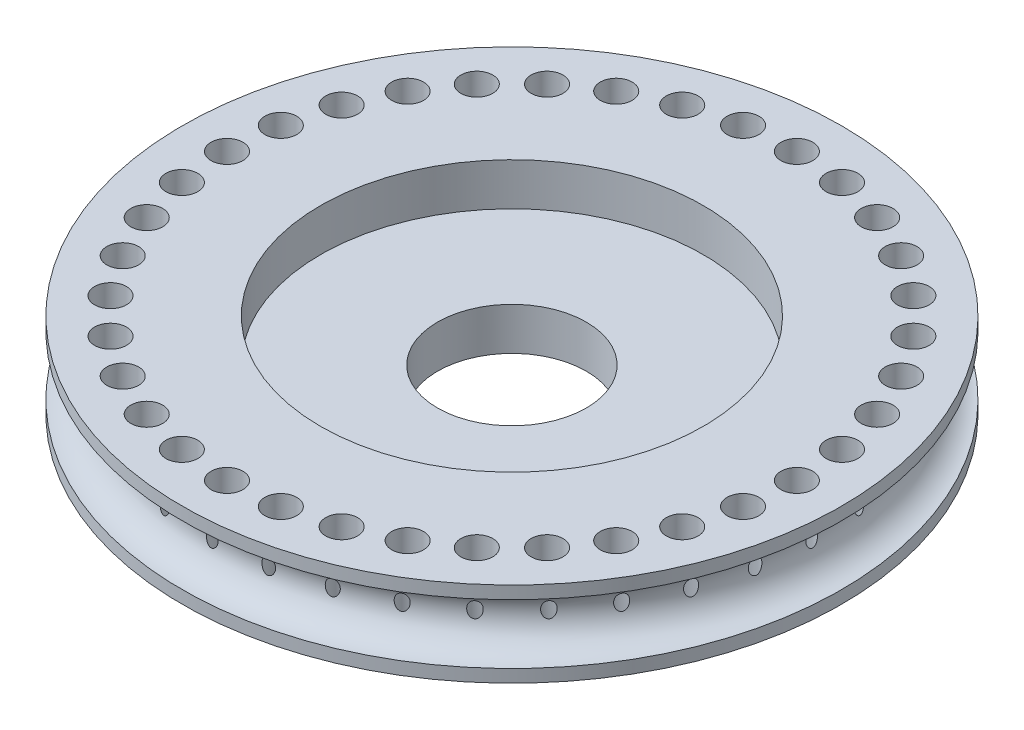
SolidWorks part; units mm, degrees
ref_plane "Front Plane" through (0, 0, 0) normal (0, 0, 1) x (1, 0, 0)
ref_plane "Top Plane" through (0, 0, 0) normal (0, 1, 0) x (1, 0, 0)
ref_plane "Right Plane" through (0, 0, 0) normal (1, 0, 0) x (0, 0, -1)
sketch "Sketch1" plane through (0, 0, 0) normal (0, 0, 1) x (1, 0, 0)
  line L0 (0, 0) -> (0, 11.2256) construction
  line L1 (0, 0) -> (-15.5, 0)
  line L2 (-15.5, 0) -> (-15.5, 0.6)
  line L3 (-15.5, 3.4) -> (-15.5, 4)
  line L4 (-15.5, 4) -> (0, 4)
  line L5 (-3.5, 4) -> (-3.5, 0)
  circle A0 centre (-15.5, 2) radius 1.4
  dimension "D5" = 15.5
  dimension "D1" = 4
  dimension "D2" = 15.5
  dimension "D3" = 0.6
  dimension "D4" = 0.6
  dimension "D6" = 3.5
revolve "Revolve1" add sketch "Sketch1" angle 360 about L0
sketch "Sketch2" plane through (0, 4, 0) normal (0, 1, 0) x (1, 0, 0)
  circle A0 centre (0, 0) radius 9
  dimension "D1" = 18
extrude "Cut-Extrude1" cut sketch "Sketch2" against normal blind 2
sketch "Sketch3" plane through (0, 4, 0) normal (0, 1, 0) x (1, 0, 0)
  line L0 (0, 0) -> (0, 15.5) construction
  circle A0 centre (0, 0) radius 15.5 construction
  circle A1 centre (0, 13.4) radius 0.75
  circle A2 centre (2.3269, 13.1964) radius 0.75
  circle A3 centre (4.5831, 12.5919) radius 0.75
  circle A4 centre (6.7, 11.6047) radius 0.75
  circle A5 centre (8.6134, 10.265) radius 0.75
  circle A6 centre (10.265, 8.6134) radius 0.75
  circle A7 centre (11.6047, 6.7) radius 0.75
  circle A8 centre (12.5919, 4.5831) radius 0.75
  circle A9 centre (13.1964, 2.3269) radius 0.75
  circle A10 centre (13.4, 0) radius 0.75
  circle A11 centre (13.1964, -2.3269) radius 0.75
  circle A12 centre (12.5919, -4.5831) radius 0.75
  circle A13 centre (11.6047, -6.7) radius 0.75
  circle A14 centre (10.265, -8.6134) radius 0.75
  circle A15 centre (8.6134, -10.265) radius 0.75
  circle A16 centre (6.7, -11.6047) radius 0.75
  circle A17 centre (4.5831, -12.5919) radius 0.75
  circle A18 centre (2.3269, -13.1964) radius 0.75
  circle A19 centre (0, -13.4) radius 0.75
  circle A20 centre (-2.3269, -13.1964) radius 0.75
  circle A21 centre (-4.5831, -12.5919) radius 0.75
  circle A22 centre (-6.7, -11.6047) radius 0.75
  circle A23 centre (-8.6134, -10.265) radius 0.75
  circle A24 centre (-10.265, -8.6134) radius 0.75
  circle A25 centre (-11.6047, -6.7) radius 0.75
  circle A26 centre (-12.5919, -4.5831) radius 0.75
  circle A27 centre (-13.1964, -2.3269) radius 0.75
  circle A28 centre (-13.4, 0) radius 0.75
  circle A29 centre (-13.1964, 2.3269) radius 0.75
  circle A30 centre (-12.5919, 4.5831) radius 0.75
  circle A31 centre (-11.6047, 6.7) radius 0.75
  circle A32 centre (-10.265, 8.6134) radius 0.75
  circle A33 centre (-8.6134, 10.265) radius 0.75
  circle A34 centre (-6.7, 11.6047) radius 0.75
  circle A35 centre (-4.5831, 12.5919) radius 0.75
  circle A36 centre (-2.3269, 13.1964) radius 0.75
  point P80 (0, 0)
  dimension "D1" = 1.5
  dimension "D2" = 13.4
  dimension "D3" = 36
extrude "Cut-Extrude2" cut sketch "Sketch3" against normal through all
